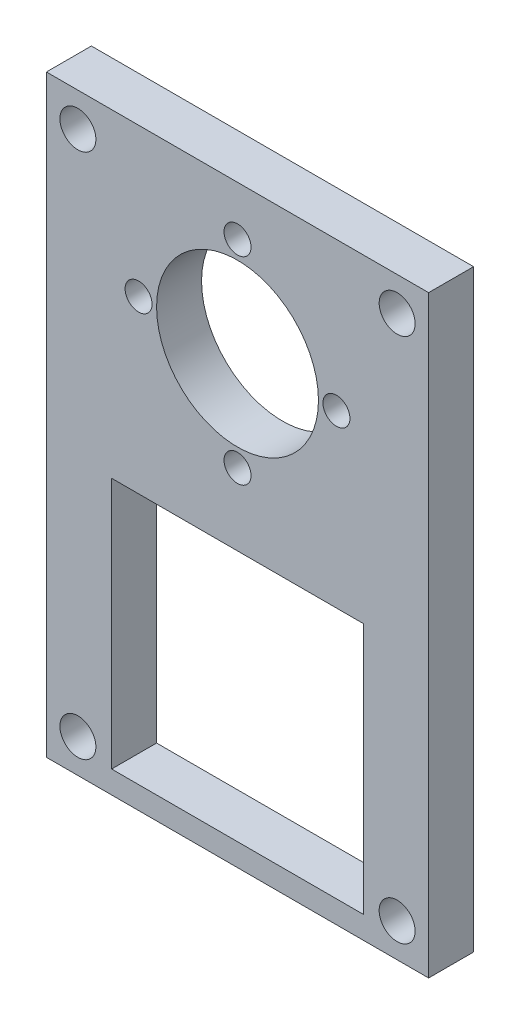
SolidWorks part; units mm, degrees
ref_plane "Front Plane" through (0, 0, 0) normal (0, 0, 1) x (1, 0, 0)
ref_plane "Top Plane" through (0, 0, 0) normal (0, 1, 0) x (1, 0, 0)
ref_plane "Right Plane" through (0, 0, 0) normal (1, 0, 0) x (0, 0, -1)
sketch "Sketch1" plane through (0, 0, 0) normal (0, 0, 1) x (1, 0, 0)
  line L1 (-21.25, 33) -> (21.25, 33)
  line L2 (-21.25, 33) -> (-21.25, -33)
  line L3 (-21.25, -33) -> (21.25, -33)
  line L4 (21.25, 33) -> (21.25, -33)
  line L5 (-21.25, 33) -> (21.25, -33) construction
  line L6 (-21.25, -33) -> (21.25, 33) construction
  point P0 (0, 0)
  dimension "D1" = 42.5
  dimension "D2" = 66
extrude "Boss-Extrude1" add sketch "Sketch1" along normal blind 5
sketch "Sketch2" plane through (0, 0, 5) normal (0, 0, 1) x (1, 0, 0)
  circle A0 centre (0, 16.5) radius 9
  circle A1 centre (0, 27.5) radius 1.5
  circle A2 centre (11, 16.5) radius 1.5
  circle A3 centre (-11, 16.5) radius 1.5
  circle A4 centre (0, 5.5) radius 1.5
  dimension "D1" = 18
  dimension "D4" = 3
  dimension "D7" = 3
  dimension "D8" = 3
  dimension "D9" = 3
  dimension "D2" = 16.5
  dimension "D3" = 21.25
  dimension "D5" = 11
  dimension "D6" = 21.25
  dimension "D10" = 11
  dimension "D11" = 11
  dimension "D12" = 11
  dimension "D13" = 0
  dimension "D14" = 11
  dimension "D15" = 21.25
extrude "Cut-Extrude1" cut sketch "Sketch2" against normal through all
sketch "Sketch3" plane through (0, 0, 5) normal (0, 0, 1) x (1, 0, 0)
  line L3 (-14, -2.5) -> (14, -2.5)
  line L4 (-14, -2.5) -> (-14, -30.5)
  line L5 (-14, -30.5) -> (14, -30.5)
  line L6 (14, -2.5) -> (14, -30.5)
  line L7 (-14, -2.5) -> (14, -30.5) construction
  line L8 (-14, -30.5) -> (14, -2.5) construction
  point P0 (0, -16.5)
  dimension "D1" = 28
  dimension "D2" = 28
  dimension "D3" = 16.5
  dimension "D4" = 21.25
extrude "Cut-Extrude2" cut sketch "Sketch3" against normal through all
sketch "Sketch4" plane through (0, 0, 5) normal (0, 0, 1) x (1, 0, 0)
  circle A0 centre (-17.75, 29.25) radius 2
  circle A1 centre (17.75, 29.25) radius 2
  circle A2 centre (-17.75, -29.25) radius 2
  circle A3 centre (17.75, -29.25) radius 2
  dimension "D3" = 4
  dimension "D4" = 4
  dimension "D5" = 4
  dimension "D6" = 4
  dimension "D1" = 3.5
  dimension "D2" = 3.5
  dimension "D7" = 3.5
  dimension "D8" = 3.75
  dimension "D9" = 3.75
  dimension "D10" = 3.75
  dimension "D11" = 3.5
  dimension "D12" = 3.75
extrude "Cut-Extrude3" cut sketch "Sketch4" against normal through all
